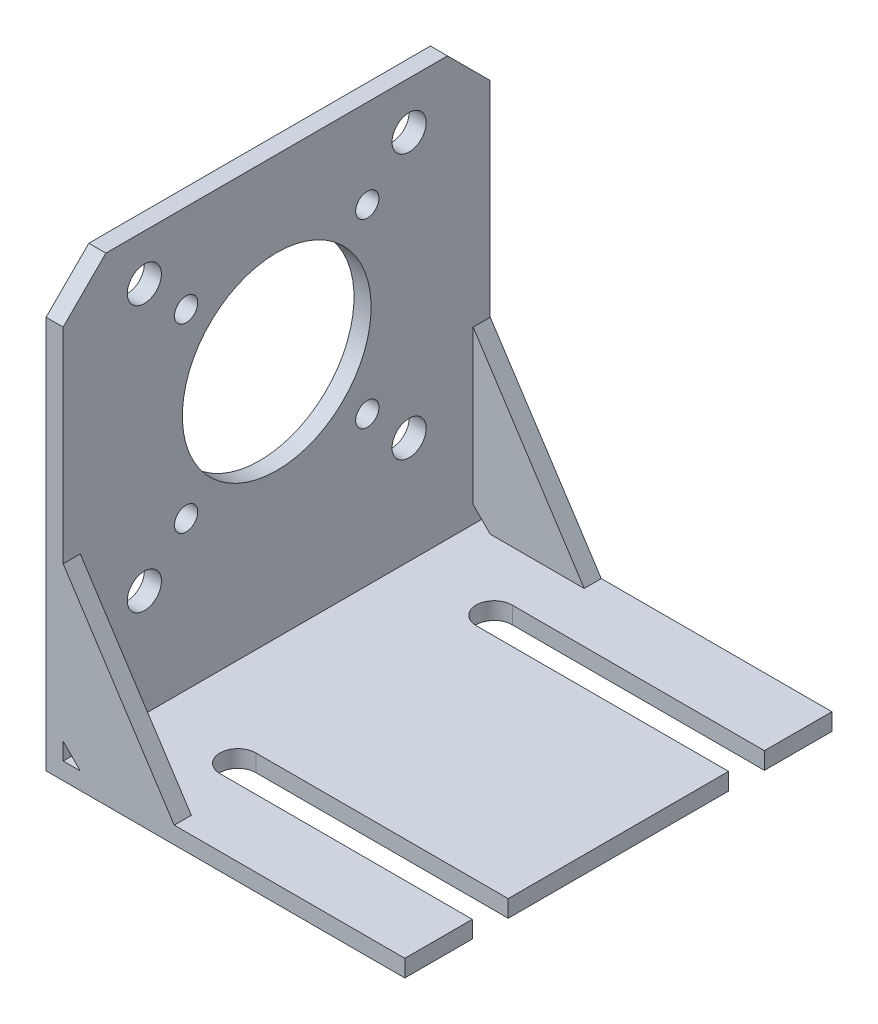
SolidWorks part; units mm, degrees
ref_plane "Front" through (0, 0, 0) normal (0, 0, 1) x (1, 0, 0)
ref_plane "Top" through (0, 0, 0) normal (0, 1, 0) x (1, 0, 0)
ref_plane "Right" through (0, 0, 0) normal (1, 0, 0) x (0, 0, -1)
sketch "Sketch1" plane through (0, 0, 0) normal (0, 0, 1) x (1, 0, 0)
  line L0 (0, 0) -> (0, 51)
  line L1 (0, 51) -> (2, 51)
  line L2 (2, 51) -> (2, 2)
  line L3 (2, 2) -> (53, 2)
  line L4 (53, 2) -> (53, 0)
  line L5 (53, 0) -> (0, 0)
  dimension "D1" = 51
  dimension "D2" = 53
  dimension "D3" = 2
  dimension "D4" = 2
extrude "Boss-Extrude1" add sketch "Sketch1" along normal blind 50
sketch "Sketch2" plane through (2, 0, 0) normal (1, 0, 0) x (0, 0, -1)
  line L0 (-25, 51) -> (-25, 2) construction
  line L1 (-50, 51) -> (0, 51) construction
  line L2 (-50, 2) -> (0, 2) construction
  line L3 (-50, 30) -> (0, 30) construction
  line L4 (-50, 2) -> (-50, 51) construction
  line L5 (0, 2) -> (0, 51) construction
  line L6 (-40.5, 51) -> (-40.5, 2) construction
  line L7 (-9.5, 51) -> (-9.5, 2) construction
  line L8 (-50, 14.5) -> (0, 14.5) construction
  line L9 (-50, 45.5) -> (0, 45.5) construction
  circle A0 centre (-25, 30) radius 11.05
  circle A1 centre (-40.5, 45.6404) radius 2
  circle A2 centre (-9.5, 45.5) radius 2
  circle A3 centre (-40.5, 14.5) radius 2
  circle A4 centre (-9.5, 14.5) radius 2
  dimension "D6" = 4
  dimension "D7" = 4
  dimension "D8" = 4
  dimension "D9" = 4
  dimension "D10" = 22.1
  dimension "D1" = 21
  dimension "D2" = 15.5
  dimension "D3" = 15.5
  dimension "D4" = 15.5
  dimension "D5" = 15.5
extrude "Cut-Extrude1" cut sketch "Sketch2" against normal through all
sketch "Sketch3" plane through (0, 2, 0) normal (0, 1, 0) x (1, 0, 0)
  line L0 (2, -25) -> (53, -25) construction
  line L1 (2, -50) -> (2, 0) construction
  line L2 (53, -50) -> (53, 0) construction
  line L3 (2, -40) -> (53, -40) construction
  line L4 (53, -50) -> (2, -50) construction
  line L5 (27.5, -50) -> (27.5, 0) construction
  line L6 (53, 0) -> (2, 0) construction
  line L7 (2, -10) -> (53, -10) construction
  line L9 (12.4553, -12.1) -> (42.5447, -12.1)
  line L11 (12.5, -7.9005) -> (42.5, -7.9005)
  line L13 (27.5, -7.9005) -> (27.5, -12.1) construction
  line L14 (12.4553, -10) -> (42.5447, -10) construction
  line L15 (12.5, -42.0995) -> (42.5, -42.0995)
  line L17 (12.4553, -37.9) -> (42.5447, -37.9)
  line L19 (27.5, -37.9) -> (27.5, -42.0995) construction
  line L20 (12.4553, -40) -> (42.5447, -40) construction
  arc A0 (42.5, -7.9005) -> (42.5447, -12.1) centre (42.5447, -10) cw
  arc A1 (12.4553, -12.1) -> (12.5, -7.9005) centre (12.4553, -10) cw
  arc A2 (12.5, -42.0995) -> (12.4553, -37.9) centre (12.4553, -40) cw
  arc A3 (42.5447, -37.9) -> (42.5, -42.0995) centre (42.5447, -40) cw
  point P16 (27.5, -10)
  point P20 (27.5, -40)
  dimension "D3" = 2.1
  dimension "D4" = 2.1
  dimension "D5" = 30
  dimension "D6" = 30
  dimension "D7" = 10.4553
  dimension "D8" = 10.4553
  dimension "D1" = 15
  dimension "D2" = 15
extrude "Cut-Extrude2" cut sketch "Sketch3" against normal blind 50
sketch "Sketch5" plane through (0, 0, 50) normal (0, 0, 1) x (1, 0, 0)
  line L0 (2, 22) -> (2, 4)
  line L1 (2, 2) -> (2, 51) construction
  line L2 (2, 4) -> (4, 2)
  line L3 (53, 2) -> (2, 2) construction
  line L4 (4, 2) -> (15, 2)
  line L5 (15, 2) -> (2, 22)
  dimension "D1" = 2
  dimension "D2" = 2
  dimension "D3" = 20
  dimension "D4" = 13
extrude "Boss-Extrude2" add sketch "Sketch5" against normal blind 2
sketch "Sketch6" plane through (0, 0, 0) normal (0, 0, -1) x (-1, 0, 0)
  line L0 (-4, 2) -> (-2, 4)
  line L1 (-2, 2) -> (-53, 2) construction
  line L2 (-2, 51) -> (-2, 2) construction
  line L3 (-2, 4) -> (-2, 22)
  line L4 (-2, 22) -> (-15, 2)
  line L5 (-15, 2) -> (-4, 2)
  dimension "D1" = 2
  dimension "D2" = 20
  dimension "D3" = 2
  dimension "D4" = 13
extrude "Boss-Extrude3" add sketch "Sketch6" against normal blind 2
chamfer "Chamfer1" distance 5 angle 45 4 edges at (53, 1, 0) (53, 1, 50) (1, 51, 0) (1, 51, 50)
sketch "Sketch8" plane through (0, 0, 0) normal (-1, 0, 0) x (0, 0, 1)
  line L0 (25, 30) -> (35.6066, 19.3934) construction
  circle A0 centre (35.6066, 19.3934) radius 1.3612
  circle A1 centre (14.3934, 19.3934) radius 1.3612
  circle A2 centre (14.3934, 40.6066) radius 1.3612
  circle A3 centre (35.6066, 40.6066) radius 1.3612
  point P13 (25, 30)
  dimension "D2" = 2.7223
  dimension "D1" = 15
  dimension "D3" = 4
extrude "Cut-Extrude3" cut sketch "Sketch8" against normal blind 10
sketch "Sketch9" plane through (0, 2, 0) normal (0, 1, 0) x (1, 0, 0)
  line L0 (2, -25) -> (42, -25) construction
  line L1 (2, -50) -> (2, 0) construction
  line L2 (42, -25) -> (42, -50) construction
  line L3 (48, -50) -> (15, -50) construction
  line L5 (42, -50) -> (68.1863, -50)
  line L6 (42, -50) -> (42, 0)
  line L7 (42, 0) -> (68.1863, 0)
  line L8 (68.1863, -50) -> (68.1863, 0)
  dimension "D1" = 40
extrude "Cut-Extrude4" cut sketch "Sketch9" against normal blind 10
